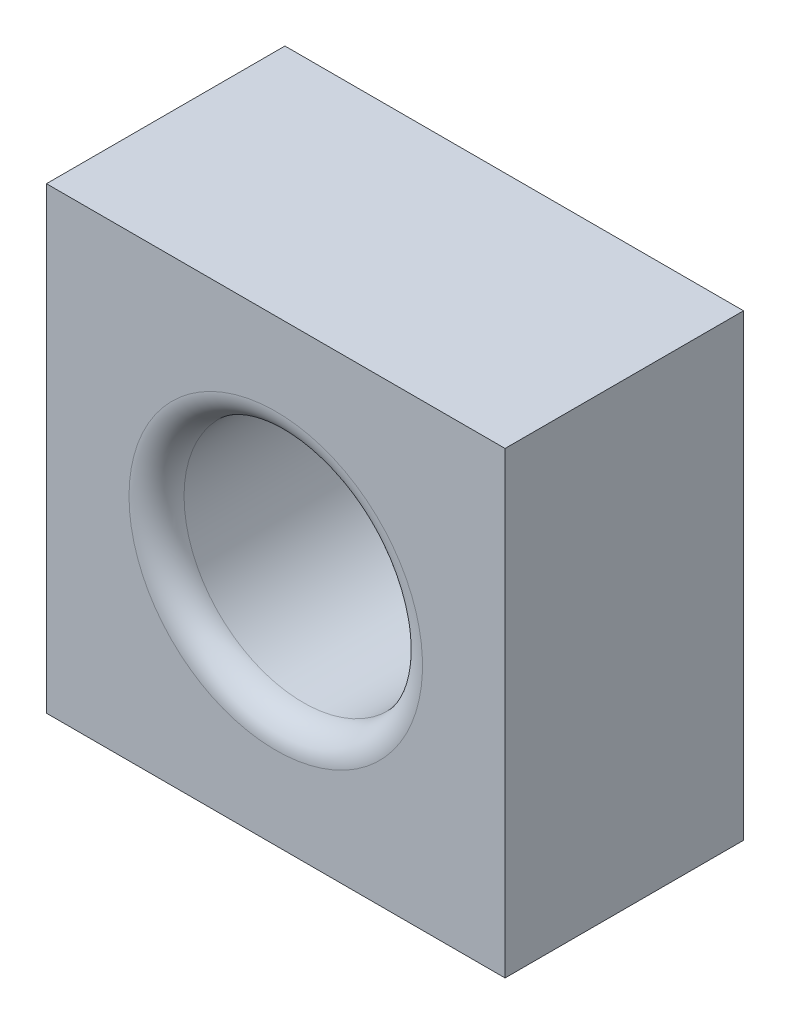
SolidWorks part; units mm, degrees
ref_plane "Front Plane" through (0, 0, 0) normal (0, 0, 1) x (1, 0, 0)
ref_plane "Top Plane" through (0, 0, 0) normal (0, 1, 0) x (1, 0, 0)
ref_plane "Right Plane" through (0, 0, 0) normal (1, 0, 0) x (0, 0, -1)
sketch "Sketch1" plane through (0, 0, 0) normal (0, 0, 1) x (1, 0, 0)
  line L1 (-12.5, -12.5) -> (12.5, -12.5)
  line L2 (-12.5, -12.5) -> (-12.5, 12.5)
  line L3 (-12.5, 12.5) -> (12.5, 12.5)
  line L4 (12.5, -12.5) -> (12.5, 12.5)
  line L5 (-12.5, -12.5) -> (12.5, 12.5) construction
  line L6 (-12.5, 12.5) -> (12.5, -12.5) construction
  circle A0 centre (0, 0) radius 6.5
  point P0 (0, 0)
  dimension "D1" = 13
  dimension "D2" = 25
extrude "Boss-Extrude1" add sketch "Sketch1" along normal blind 13
fillet "Fillet1" radius 1.5 1 edges at (6.5, 0, 13)
